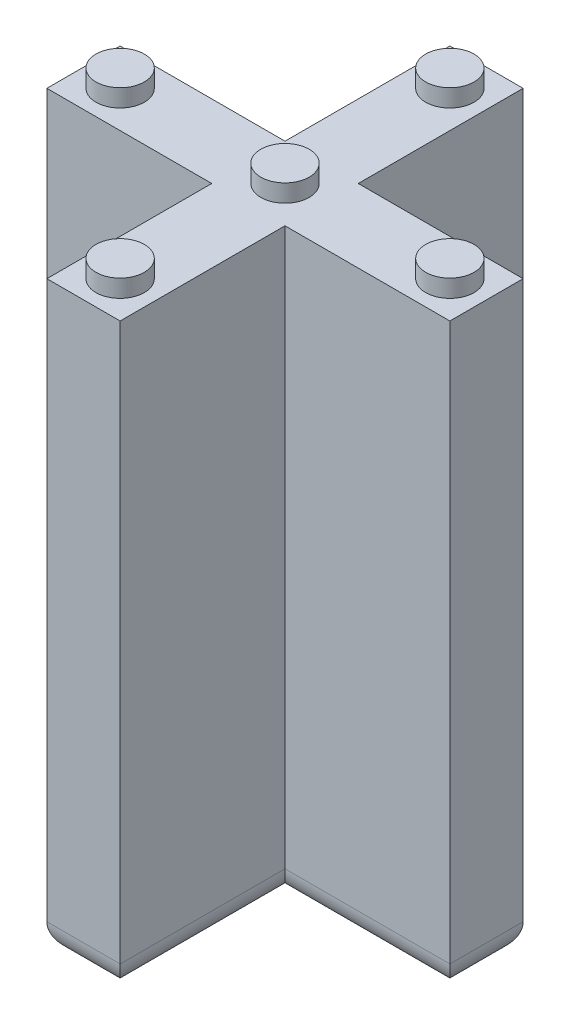
SolidWorks part; units mm, degrees
ref_plane "Front Plane" through (0, 0, 0) normal (0, 0, 1) x (1, 0, 0)
ref_plane "Top Plane" through (0, 0, 0) normal (0, 1, 0) x (1, 0, 0)
ref_plane "Right Plane" through (0, 0, 0) normal (1, 0, 0) x (0, 0, -1)
sketch "Sketch1" plane through (0, 0, 0) normal (0, 1, 0) x (1, 0, 0)
  line L1 (-2.5, -13.75) -> (2.5, -13.75)
  line L2 (-2.5, -13.75) -> (-2.5, -2.5)
  line L3 (-2.5, 13.75) -> (2.5, 13.75)
  line L4 (2.5, -13.75) -> (2.5, -2.5)
  line L7 (-13.75, -2.5) -> (-2.5, -2.5)
  line L8 (-13.75, -2.5) -> (-13.75, 2.5)
  line L9 (-13.75, 2.5) -> (-2.5, 2.5)
  line L10 (13.75, -2.5) -> (13.75, 2.5)
  line L15 (3.65, 0) -> (2.5, 0)
  line L16 (-55, 0) -> (55, 0) construction
  line L17 (2.5, -2.5) -> (13.75, -2.5)
  line L21 (2.5, 2.5) -> (13.75, 2.5)
  line L22 (-2.5, 2.5) -> (-2.5, 13.75)
  line L23 (2.5, -0.4545) -> (2.5, 0)
  line L24 (2.5, 2.5) -> (2.5, 13.75)
  point P0 (0, 0)
  point P6 (0, 0)
  dimension "D1" = 5
  dimension "D2" = 5
  dimension "D3" = 27.5
  dimension "D4" = 27.5
extrude "Boss-Extrude1" add sketch "Sketch1" along normal blind 40
sketch "Sketch2" plane through (0, 40, 0) normal (0, 1, 0) x (1, 0, 0)
  line L0 (0, 0) -> (0, 3.8481)
  line L1 (0, -15.125) -> (0, 15.125) construction
  line L2 (0, 3.8481) -> (0, 0)
  line L3 (0, 0) -> (2.8705, 0)
  line L4 (-15.125, 0) -> (15.125, 0) construction
  line L5 (13.75, 0) -> (11.25, 0)
  line L6 (13.75, -2.5) -> (13.75, 2.5) construction
  line L7 (-2.5, 13.75) -> (2.5, 13.75) construction
  circle A0 centre (11.25, 0) radius 1.65
  circle A1 centre (-11.25, 0) radius 1.65
  circle A2 centre (0, 11.25) radius 1.65
  circle A3 centre (0, -11.25) radius 1.65
  circle A4 centre (0, 0) radius 1.65
  dimension "D2" = 2.5
  dimension "D1" = 2.5
extrude "Boss-Extrude2" add sketch "Sketch2" along normal blind 1.2
fillet "Fillet2" radius 2 12 edges at (2.5, 0, -8.125) (0, 0, -13.75) (-2.5, 0, -8.125) (-8.125, 0, -2.5) (-13.75, 0, 0) (-8.125, 0, 2.5) (-2.5, 0, 8.125) (0, 0, 13.75) (2.5, 0, 8.125) (8.125, 0, 2.5) (13.75, 0, 0) (8.125, 0, -2.5)
